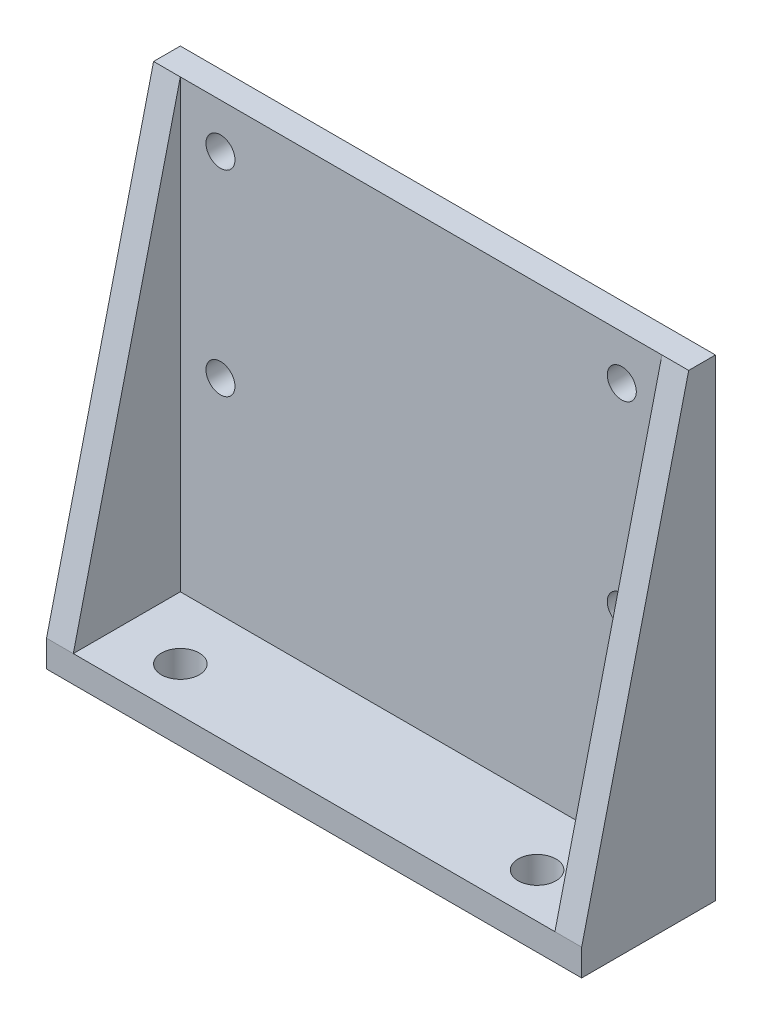
SolidWorks part; units mm, degrees
ref_plane "Front Plane" through (0, 0, 0) normal (0, 0, 1) x (1, 0, 0)
ref_plane "Top Plane" through (0, 0, 0) normal (0, 1, 0) x (1, 0, 0)
ref_plane "Right Plane" through (0, 0, 0) normal (1, 0, 0) x (0, 0, -1)
sketch "Sketch1" plane through (0, 0, 0) normal (0, 1, 0) x (1, 0, 0)
  line L0 (30, 15) -> (30, 0) construction
  line L1 (0, 0) -> (60, 0)
  line L2 (0, 0) -> (0, 15)
  line L3 (0, 15) -> (60, 15)
  line L4 (60, 0) -> (60, 15)
  circle A0 centre (10, 5) radius 2.125
  circle A1 centre (50, 5) radius 2.125
  dimension "D2" = 4.25
  dimension "D1" = 10
  dimension "D3" = 5
  dimension "D4" = 10
  dimension "D5" = 20
extrude "Boss-Extrude1" add sketch "Sketch1" along normal blind 3
sketch "Sketch2" plane through (0, 0, -15) normal (0, 0, -1) x (-1, 0, 0)
  line L0 (-30, 53) -> (-30, 3) construction
  line L1 (-60, 3) -> (0, 3)
  line L2 (-60, 3) -> (-60, 53)
  line L3 (-60, 53) -> (0, 53)
  line L4 (0, 3) -> (0, 53)
  circle A0 centre (-52.5, 48) radius 1.625
  circle A1 centre (-52.5, 26) radius 1.625
  circle A2 centre (-7.5, 26) radius 1.625
  circle A3 centre (-7.5, 48) radius 1.625
  dimension "D2" = 3.25
  dimension "D4" = 3.25
  dimension "D1" = 50
  dimension "D3" = 22.5
  dimension "D5" = 22
  dimension "D6" = 5
extrude "Boss-Extrude2" add sketch "Sketch2" against normal blind 3
sketch "Sketch3" plane through (0, 0, 0) normal (-1, 0, 0) x (0, 0, 1)
  line L0 (-12, 53) -> (0, 3)
  line L1 (0, 3) -> (-12, 3)
  line L2 (-12, 3) -> (-12, 53)
extrude "Boss-Extrude3" add sketch "Sketch3" against normal blind 3
ref_plane "Plane1" through (30, 0, 0) normal (-1, 0, 0) x (0, 0, 1)
mirror "Mirror1" about plane through (30, 0, 0) normal (-1, 0, 0) of "Boss-Extrude3"
